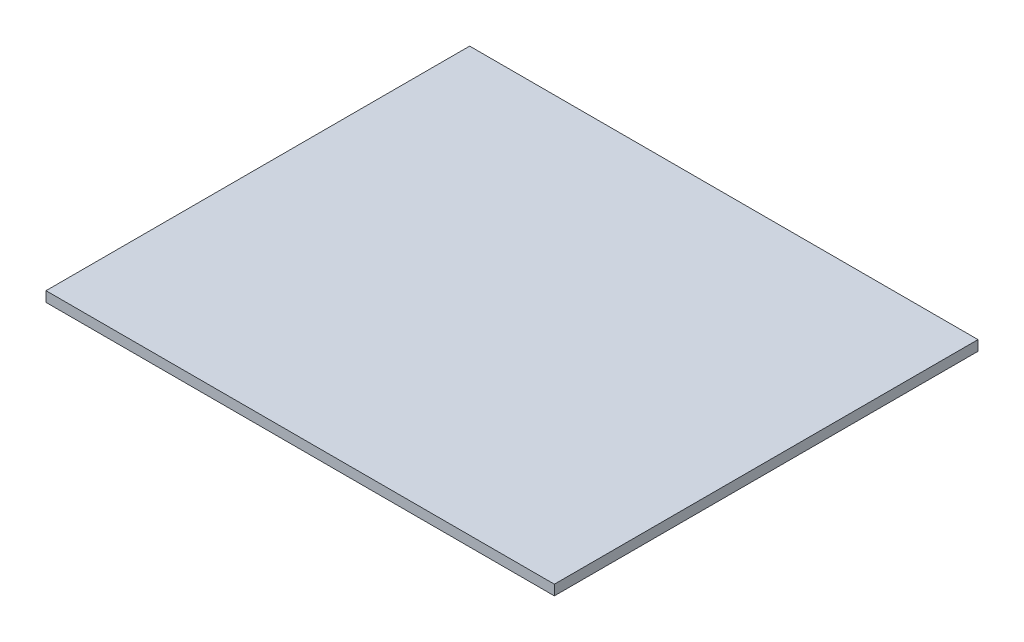
SolidWorks part; units mm, degrees
material "Aluminum Bronze"
ref_plane "Front Plane" through (0, 0, 0) normal (0, 0, 1) x (1, 0, 0)
ref_plane "Top Plane" through (0, 0, 0) normal (0, 1, 0) x (1, 0, 0)
ref_plane "Right Plane" through (0, 0, 0) normal (1, 0, 0) x (0, 0, -1)
sketch "Sketch1" plane through (0, 0, 0) normal (0, 1, 0) x (1, 0, 0)
  line L1 (-30, 25) -> (30, 25)
  line L2 (-30, 25) -> (-30, -25)
  line L3 (-30, -25) -> (30, -25)
  line L4 (30, 25) -> (30, -25)
  line L5 (-30, 25) -> (30, -25) construction
  line L6 (-30, -25) -> (30, 25) construction
  point P0 (0, 0)
  dimension "D1" = 60
  dimension "D2" = 50
extrude "Boss-Extrude1" add sketch "Sketch1" along normal blind 1.2
